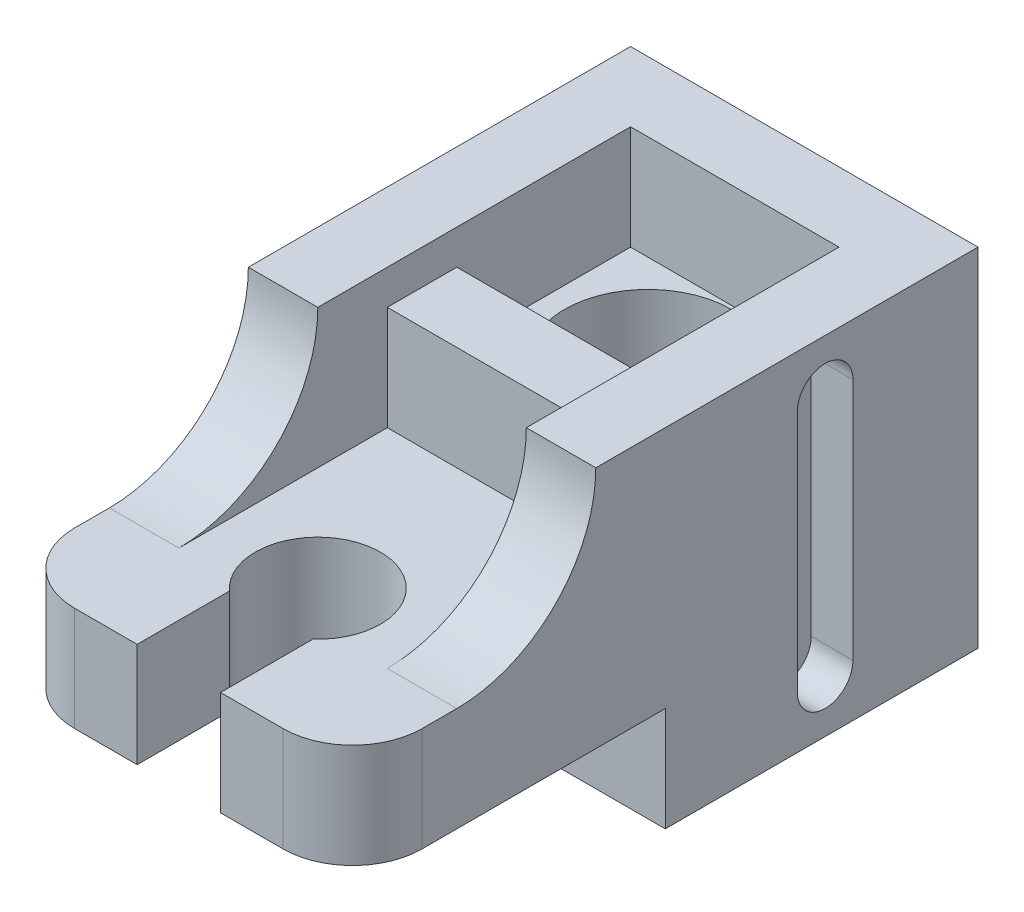
SolidWorks part; units mm, degrees
ref_plane "Front Plane" through (0, 0, 0) normal (0, 0, 1) x (1, 0, 0)
ref_plane "Top Plane" through (0, 0, 0) normal (0, 1, 0) x (1, 0, 0)
ref_plane "Right Plane" through (0, 0, 0) normal (1, 0, 0) x (0, 0, -1)
sketch "Sketch6" plane through (0, 0, 0) normal (1, 0, 0) x (0, 0, -1)
  line L0 (0, 0) -> (45, 0)
  line L1 (45, 0) -> (45, 50)
  line L2 (45, 50) -> (-10, 50)
  line L3 (-30, 30) -> (-45, 30)
  line L4 (-45, 30) -> (-45, 15)
  line L5 (-45, 15) -> (0, 15)
  line L6 (0, 15) -> (0, 0)
  arc A0 (-10, 50) -> (-30, 30) centre (-30, 50) cw
  dimension "D1" = 45
  dimension "D4" = 20
  dimension "D2" = 50
  dimension "D3" = 75
  dimension "D5" = 15
  dimension "D6" = 45
extrude "Boss-Extrude3" add sketch "Sketch6" along normal mid plane 50
sketch "Sketch8" plane through (0, 0, 0) normal (1, 0, 0) x (0, 0, -1)
  line L0 (35, 50) -> (35, 35)
  line L1 (45, 50) -> (-10, 50) construction
  line L2 (35, 35) -> (10, 35)
  line L3 (10, 35) -> (10, 45)
  line L4 (10, 45) -> (0, 45)
  line L5 (0, 45) -> (0, 30)
  line L6 (0, 30) -> (-30, 30)
  line L7 (35, 50) -> (-10, 50)
  arc A0 (-30, 30) -> (-10, 50) centre (-30, 50) ccw construction
  arc A1 (-30, 30) -> (-10, 50) centre (-30, 50) ccw
  dimension "D1" = 10
  dimension "D2" = 15
  dimension "D3" = 25
  dimension "D4" = 10
  dimension "D5" = 15
extrude "Cut-Extrude3" cut sketch "Sketch8" against normal mid plane 30
sketch "Sketch9" plane through (0, 0, 0) normal (0, 1, 0) x (1, 0, 0)
  line L0 (-6, -31.7082) -> (-6, -45)
  line L1 (25, -45) -> (-25, -45) construction
  line L2 (6, -31.7082) -> (6, -45)
  line L4 (15, 10) -> (15, 35) construction
  line L9 (-6, -45) -> (6, -45)
  circle A0 centre (0, 22.5) radius 12
  circle A1 centre (0, -25) radius 9
  point P13 (15, 22.5)
  dimension "D1" = 12
  dimension "D2" = 18
  dimension "D4" = 24
  dimension "D3" = 20
extrude "Cut-Extrude4" cut sketch "Sketch9" along normal through all contours A0 | A1 | A1 L0 L9 L2
sketch "Sketch14" plane through (25, 0, 0) normal (1, 0, 0) x (0, 0, -1)
  line L0 (23, 42.5) -> (23, 7.5) construction
  line L1 (27, 42.5) -> (27, 7.5)
  line L2 (19, 42.5) -> (19, 7.5)
  line L3 (45, 0) -> (45, 50) construction
  arc A0 (27, 42.5) -> (19, 42.5) centre (23, 42.5) ccw
  arc A1 (19, 7.5) -> (27, 7.5) centre (23, 7.5) ccw
  point P2 (23, 25)
  point P9 (45, 25)
  dimension "D3" = 4
  dimension "D1" = 22
  dimension "D2" = 35
extrude "Cut-Extrude5" cut sketch "Sketch14" against normal blind 6
mirror "Mirror1" about plane through (0, 0, 0) normal (1, 0, 0) of "Cut-Extrude5"
fillet "Fillet2" radius 10 2 edges at (25, 22.5, 45) (-25, 22.5, 45)
